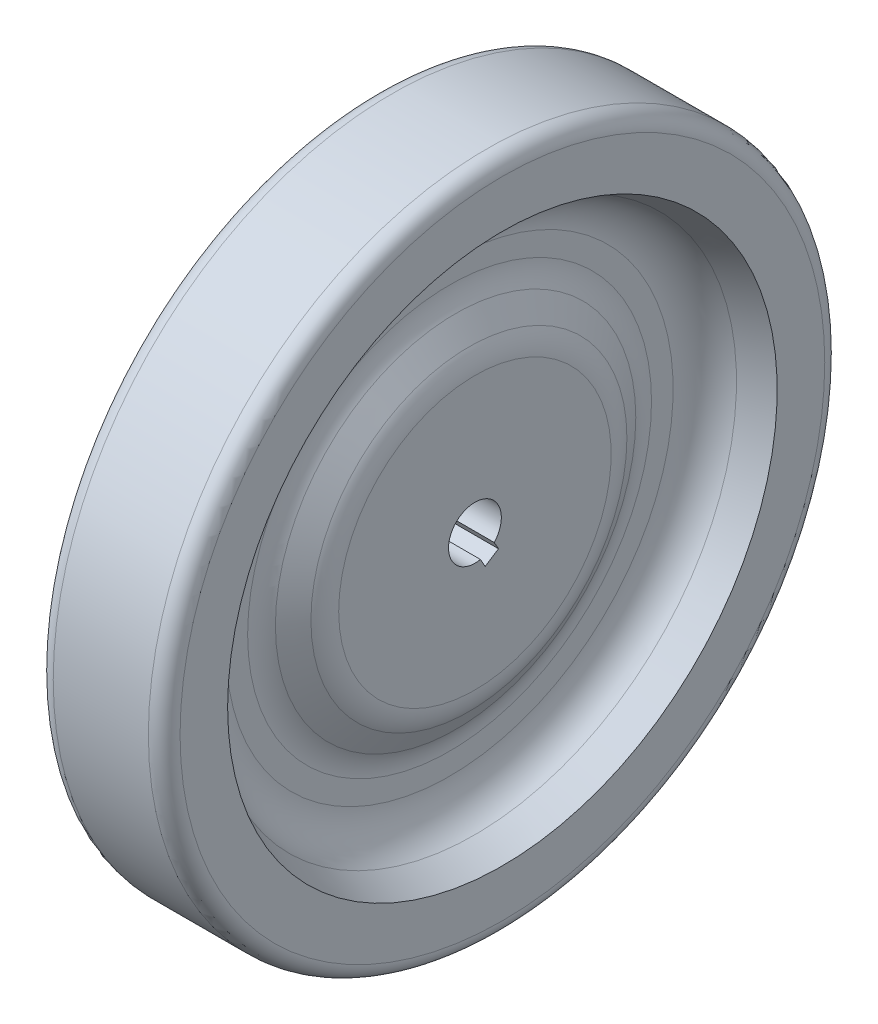
SolidWorks part; units mm, degrees
ref_plane "Front Plane" through (0, 0, 0) normal (0, 0, 1) x (1, 0, 0)
ref_plane "Top Plane" through (0, 0, 0) normal (0, 1, 0) x (1, 0, 0)
ref_plane "Right Plane" through (0, 0, 0) normal (1, 0, 0) x (0, 0, -1)
sketch "Sketch1" plane through (0, 0, 0) normal (0, 0, 1) x (1, 0, 0)
  line L0 (-10.795, 0) -> (-10.795, 40.9323)
  line L1 (-8.9852, 47.4664) -> (-4.9848, 54.1336)
  line L2 (-3.175, 60.6677) -> (-3.175, 67.1709)
  line L3 (0, 0) -> (0, 101.6) construction
  line L4 (-14.2875, 101.6) -> (14.2875, 101.6)
  line L5 (-19.05, 82.55) -> (-19.05, 0) construction
  line L6 (-19.05, 82.55) -> (-10.6362, 78.74)
  line L7 (19.05, 82.55) -> (19.05, 0) construction
  line L8 (19.05, 82.55) -> (10.6362, 78.74)
  line L9 (3.175, 60.6677) -> (3.175, 67.1709)
  line L10 (8.9852, 47.4664) -> (4.9848, 54.1336)
  line L11 (10.795, 0) -> (10.795, 40.9323)
  line L12 (-10.795, 0) -> (10.795, 0)
  line L13 (-19.05, 82.55) -> (-19.05, 96.8375)
  line L14 (19.05, 82.55) -> (19.05, 96.8375)
  arc A2 (8.9852, 47.4664) -> (10.795, 40.9323) centre (-1.905, 40.9323) cw
  arc A3 (-10.795, 40.9323) -> (-8.9852, 47.4664) centre (1.905, 40.9323) cw
  arc A4 (-4.9848, 54.1336) -> (-3.175, 60.6677) centre (-15.875, 60.6677) ccw
  arc A5 (3.175, 60.6677) -> (4.9848, 54.1336) centre (15.875, 60.6677) ccw
  arc A6 (10.6362, 78.74) -> (3.175, 67.1709) centre (15.875, 67.1709) ccw
  arc A7 (-10.6362, 78.74) -> (-3.175, 67.1709) centre (-15.875, 67.1709) cw
  arc A8 (19.05, 96.8375) -> (14.2875, 101.6) centre (14.2875, 96.8375) ccw
  arc A9 (-19.05, 96.8375) -> (-14.2875, 101.6) centre (-14.2875, 96.8375) cw
  point P21 (10.795, 44.45)
  point P24 (-10.795, 44.45)
  point P27 (-3.175, 57.15)
  point P30 (3.175, 57.15)
  point P33 (3.175, 75.3614)
  point P36 (-3.175, 75.3614)
  dimension "D9" = 12.7
  dimension "D10" = 3.81
  dimension "D1" = 101.6
  dimension "D2" = 7.62
  dimension "D3" = 19.05
  dimension "D4" = 3.175
  dimension "D5" = 57.15
  dimension "D6" = 12.7
  dimension "D7" = 4.7625
  dimension "D8" = 19.05
revolve "Revolve1" add sketch "Sketch1" angle 360 about L12
sketch "Sketch2" plane through (-10.795, 0, 0) normal (-1, 0, 0) x (0, 0, 1)
  line L10 (-7.6027, -7.372) -> (-3.6034, -9.958) construction
  line L11 (-7.141, -7.82) -> (-5.7923, -5.4271) construction
  line L12 (-1.6434, -7.7655) -> (-2.9922, -10.1584) construction
  line L13 (-7.0793, -7.7104) -> (-3.0726, -10.3012)
  line L14 (-7.0793, -7.7104) -> (-5.7923, -5.4271)
  line L15 (-1.6434, -7.7655) -> (-3.0726, -10.3012)
  arc A3 (-1.6434, -7.7655) -> (-5.7923, -5.4271) centre (0, 0) ccw construction
  arc A4 (-1.6434, -7.7655) -> (-5.7923, -5.4271) centre (0, 0) ccw
extrude "Cut-Extrude1" cut sketch "Sketch2" against normal through all both and the other way through all
